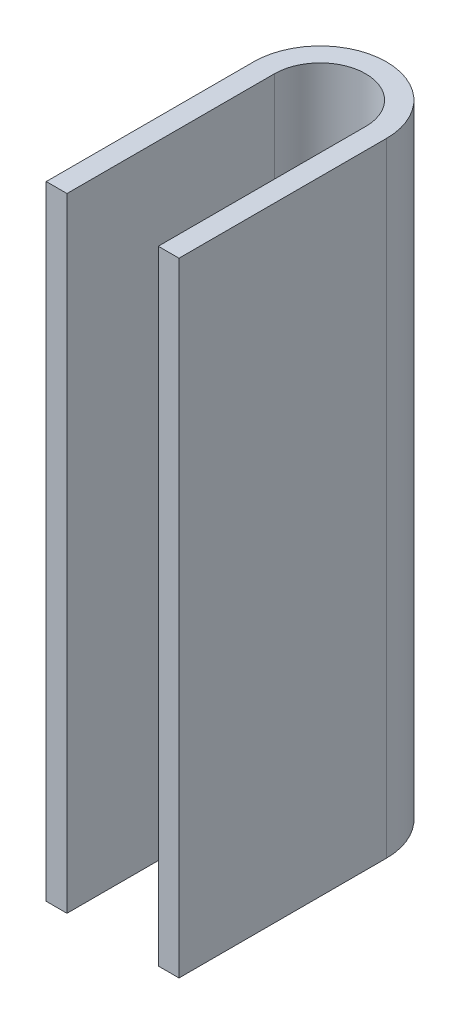
SolidWorks part; units mm, degrees
ref_plane "Front Plane" through (0, 0, 0) normal (0, 0, 1) x (1, 0, 0)
ref_plane "Top Plane" through (0, 0, 0) normal (0, 1, 0) x (1, 0, 0)
ref_plane "Right Plane" through (0, 0, 0) normal (1, 0, 0) x (0, 0, -1)
sketch "Sketch1" plane through (0, 0, 0) normal (0, 1, 0) x (1, 0, 0)
  line L0 (0, 0) -> (0, -100)
  line L1 (44, 0) -> (44, -100)
  line L2 (-10, 0) -> (-10, -100)
  line L3 (-10, -100) -> (0, -100)
  line L4 (54, 0) -> (54, -100)
  line L5 (54, -100) -> (44, -100)
  arc A0 (0, 0) -> (44, 0) centre (22, 0) cw
  arc A1 (-10, 0) -> (54, 0) centre (22, 0) cw
  dimension "D2" = 100
  dimension "D4" = 10
  dimension "D1" = 32
  dimension "D3" = 100
extrude "Boss-Extrude1" add sketch "Sketch1" along normal blind 300.5
